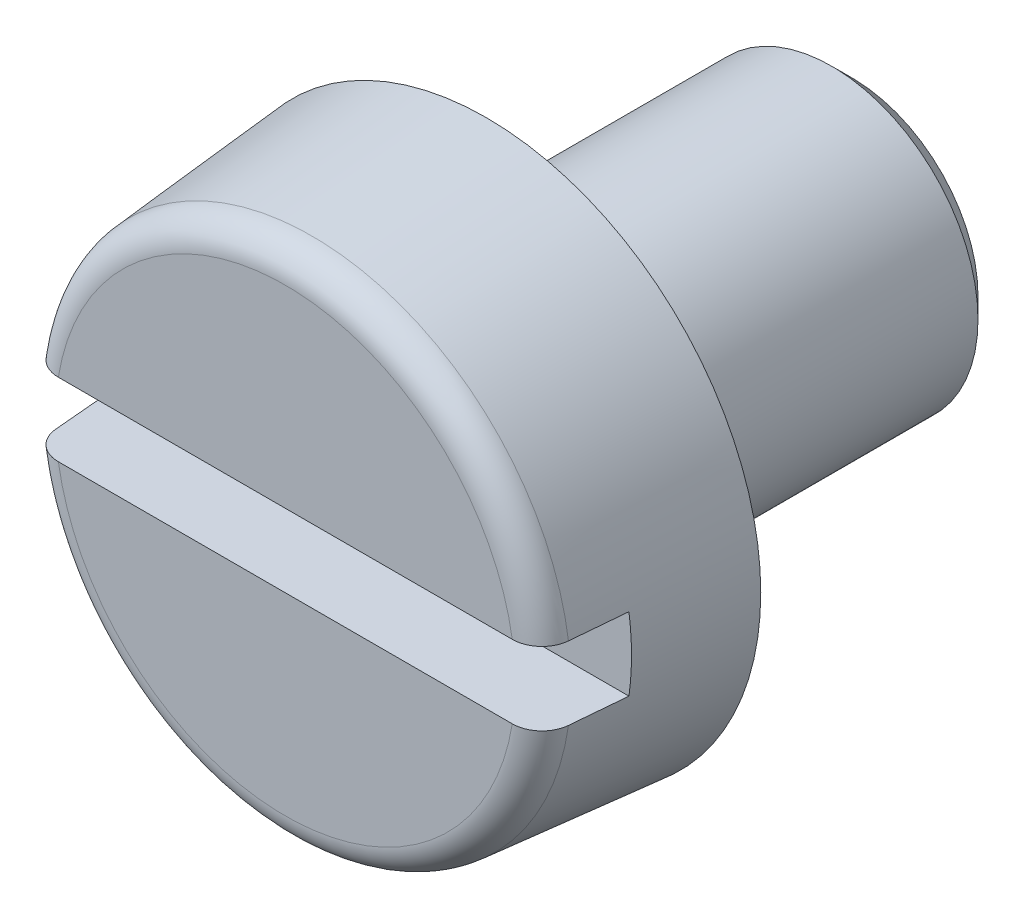
SolidWorks part; units mm, degrees
ref_plane "Přední rovina" through (0, 0, 0) normal (0, 0, 1) x (1, 0, 0)
ref_plane "Vrchní rovina" through (0, 0, 0) normal (0, 1, 0) x (1, 0, 0)
ref_plane "Pravá rovina" through (0, 0, 0) normal (1, 0, 0) x (0, 0, -1)
sketch "Skica1" plane through (0, 0, 0) normal (0, 0, 1) x (1, 0, 0)
  circle A0 centre (0, 0) radius 1.5
  dimension "dk" = 3
extrude "Vysunout1" add sketch "Skica1" along normal blind 1.1 draft 5
sketch "Skica2" plane through (0, 0, 1.1) normal (0, 0, 1) x (1, 0, 0)
  line L0 (0, 0) -> (1.5, 0) construction
  line L1 (-1.5, 0.2) -> (1.5, 0.2)
  line L2 (-1.5, 0.2) -> (-1.5, -0.2)
  line L3 (-1.5, -0.2) -> (1.5, -0.2)
  line L4 (1.5, 0.2) -> (1.5, -0.2)
  circle A2 centre (0, 0) radius 1.5 construction
  dimension "n" = 0.4
extrude "Odebrat vysunutím1" cut sketch "Skica2" against normal blind 0.45
sketch "Skica3" plane through (0, 0, 0) normal (0, 0, -1) x (-1, 0, 0)
  circle A0 centre (0, 0) radius 0.8
  dimension "M" = 1.6
extrude "Vysunout2" add sketch "Skica3" along normal blind 2
cosmetic thread "Kosmetický závit1" parameters "b"=1.9, "D2"=1.36
fillet "Zaoblit1" radius 0.1 1 edges at (0.8, 0, 0)
chamfer "Zkosit1" distance 0.112 angle 45 1 edges at (-0.8, 0, -2)
fillet "Zaoblit2" radius 0.16 4 edges at (0, 1.4038, 1.1) (0, -1.4038, 1.1)
equation "\"D1@Zkosit1\" = 0.07 * \"M@Skica3\""
equation "\"D2@Kosmetický závit1\" = 0.85 * \"M@Skica3\""
equation "\"D1@Zaoblit2\" = 0.1 * \"M@Skica3\""
